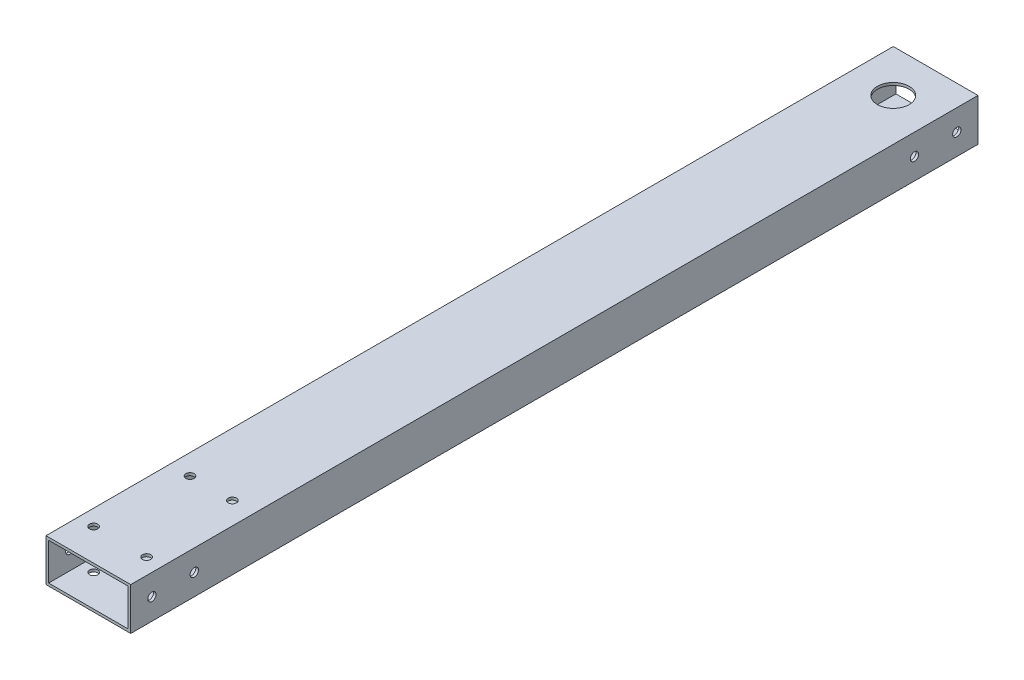
SolidWorks part; units mm, degrees
material "6061 Alloy"
ref_plane "Front Plane" through (0, 0, 0) normal (0, 0, 1) x (1, 0, 0)
ref_plane "Top Plane" through (0, 0, 0) normal (0, 1, 0) x (1, 0, 0)
ref_plane "Right Plane" through (0, 0, 0) normal (1, 0, 0) x (0, 0, -1)
sketch "Sketch1" plane through (0, 0, 0) normal (0, 0, 1) x (1, 0, 0)
  line L0 (-23.8125, 11.1125) -> (23.8125, 11.1125)
  line L2 (-25.4, 12.7) -> (25.4, 12.7)
  line L3 (-25.4, 12.7) -> (-25.4, -12.7)
  line L4 (-25.4, -12.7) -> (25.4, -12.7)
  line L5 (25.4, 12.7) -> (25.4, -12.7)
  line L10 (23.8125, 11.1125) -> (23.8125, -11.1125)
  line L11 (-23.8125, -11.1125) -> (23.8125, -11.1125)
  line L12 (-23.8125, 11.1125) -> (-23.8125, -11.1125)
  point P12 (0, 12.7)
  point P14 (25.4, 0)
  dimension "Wall Thickness" = 1.5875
  dimension "Outside Width" = 50.8
  dimension "Outside Height" = 25.4
  dimension "Inside Height" = 22.225
  dimension "Inside Width" = 47.625
sketch "Sketch2" plane through (0, 0, 0) normal (1, 0, 0) x (0, 0, -1)
  line L0 (254, 0) -> (-254, 0)
  point P4 (0, 0)
  point P7 (-254, 0)
  point P10 (254, 0)
  dimension "Length" = 508
sketch "Sketch3" plane through (0, 0, 0) normal (0, 0, 1) x (1, 0, 0)
  line L21 (25.4, 12.7) -> (-25.4, 12.7)
  line L22 (25.4, -12.7) -> (25.4, 12.7)
  line L23 (-25.4, -12.7) -> (25.4, -12.7)
  line L24 (-25.4, 12.7) -> (-25.4, -12.7)
  line L25 (25.4, 12.7) -> (-25.4, 12.7)
  line L26 (25.4, -12.7) -> (25.4, 12.7)
  line L27 (-25.4, -12.7) -> (25.4, -12.7)
  line L28 (-25.4, 12.7) -> (-25.4, -12.7)
  line L29 (23.8125, 11.1125) -> (-23.8125, 11.1125)
  line L30 (23.8125, -11.1125) -> (23.8125, 11.1125)
  line L31 (-23.8125, -11.1125) -> (23.8125, -11.1125)
  line L32 (-23.8125, 11.1125) -> (-23.8125, -11.1125)
  line L33 (23.8125, 11.1125) -> (-23.8125, 11.1125)
  line L34 (23.8125, -11.1125) -> (23.8125, 11.1125)
  line L35 (-23.8125, -11.1125) -> (23.8125, -11.1125)
  line L36 (-23.8125, 11.1125) -> (-23.8125, -11.1125)
  dimension "D1" = 0
  dimension "D2" = 0
extrude "Boss-Extrude1" add sketch "Sketch3" along normal up to vertex (254 mm away) and the other way up to vertex (254 mm away) up to point (0, 0, 254) other way up to point (0, 0, -254)
sketch "Drawing Reference" plane through (0, 0, 0) normal (1, 0, 0) x (0, 0, -1)
  line L0 (-254, 0) -> (254, 0) construction
  line L1 (0, -12.7) -> (0, 12.7) construction
  line L2 (-254, -12.7) -> (254, -12.7) construction
  line L5 (-254, 12.7) -> (254, 12.7) construction
  point P7 (-217.424, 0)
  point P8 (217.424, 0)
  dimension "D1" = 36.576
hole_wizard "#10 Clearance Hole1" positions "Sketch4" profile "Sketch5" hole size "#10" standard "ANSI Inch" end condition through all
sketch "Sketch4" plane through (25.4, 0, 0) normal (1, 0, 0) x (0, 0, -1)
  point P0 (-241.3, 0)
  point P3 (-215.9, 0)
  point P6 (215.9, 0)
  point P9 (241.3, 0)
sketch "Sketch5" plane through (25.4, 0, 241.3) normal (0, 1, 0) x (0, 0, -1)
  line L0 (0, 0) -> (0, 50.8)
  line L1 (0, 50.8) -> (2.4892, 50.8)
  line L2 (2.4892, 50.8) -> (2.4892, 0)
  line L5 (2.4892, 0) -> (0, 0)
  line L11 (0, -6.35) -> (0, 107.95) construction
  dimension "Thru Hole Dia." = 4.9784
  dimension "Thru Hole Depth" = 50.8
sketch "Sketch6" plane through (0, 12.7, 0) normal (0, 1, 0) x (1, 0, 0)
  line L1 (-13.208, -179.8675) -> (12.192, -179.8675) construction
  circle A0 centre (-13.208, -179.8675) radius 2.4892 construction
  circle A1 centre (12.192, -179.8675) radius 2.4892 construction
hole_wizard "#10 Clearance Hole2" positions "Sketch9" profile "Sketch10" hole size "#10" standard "ANSI Inch" end condition through all
sketch "Sketch9" plane through (0, 12.7, 0) normal (0, 1, 0) x (1, 0, 0)
  point P6 (-13.208, -179.8675)
  point P9 (12.192, -179.8675)
  point P12 (-15.875, -234.95)
  point P15 (15.875, -234.95)
sketch "Sketch10" plane through (-13.208, 12.7, 179.8675) normal (1, 0, 0) x (0, 0, 1)
  line L0 (0, 0) -> (0, 25.4)
  line L1 (0, 25.4) -> (2.4892, 25.4)
  line L2 (2.4892, 25.4) -> (2.4892, 0)
  line L5 (2.4892, 0) -> (0, 0)
  line L11 (0, -6.35) -> (0, 107.95) construction
  dimension "Thru Hole Dia." = 4.9784
  dimension "Thru Hole Depth" = 25.4
sketch "Sketch11" plane through (0, 12.7, 0) normal (0, 1, 0) x (1, 0, 0)
  line L0 (0, 254) -> (0, 228.6) construction
  line L1 (25.4, 254) -> (-25.4, 254) construction
  circle A0 centre (0, 228.6) radius 9.525
extrude "Cut-Extrude1" cut sketch "Sketch11" against normal through all
equation "\"D1@Drawing Reference\"=\"Outside Width@Sketch1\" * 0.72"
